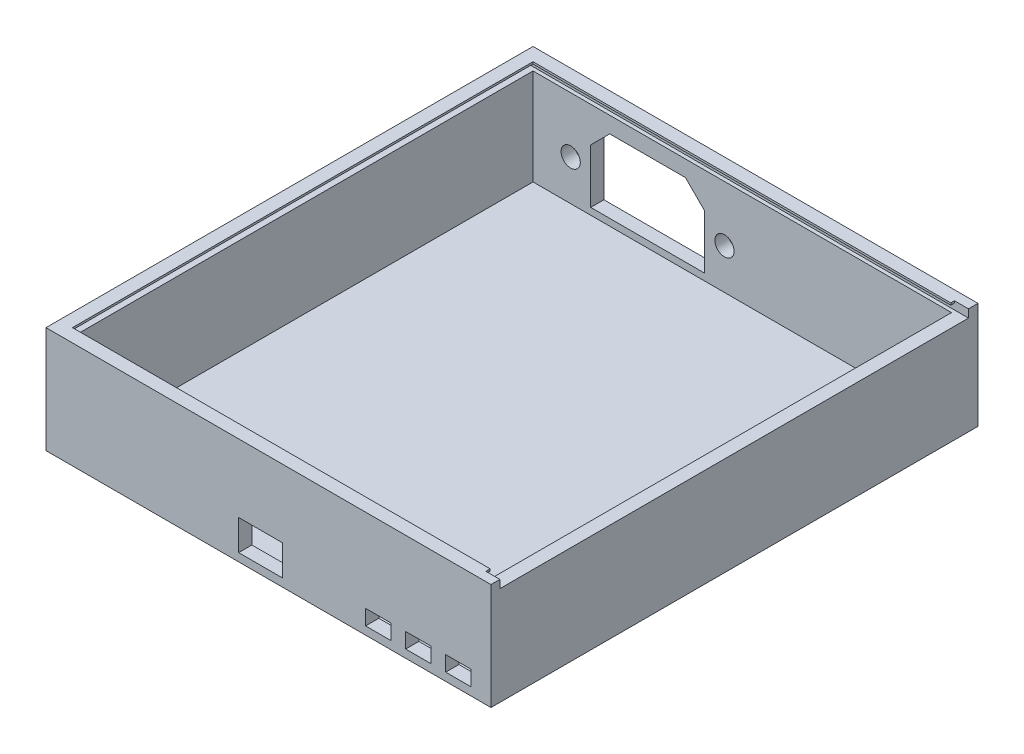
SolidWorks part; units mm, degrees
ref_plane "Front Plane" through (0, 0, 0) normal (0, 0, 1) x (1, 0, 0)
ref_plane "Top Plane" through (0, 0, 0) normal (0, 1, 0) x (1, 0, 0)
ref_plane "Right Plane" through (0, 0, 0) normal (1, 0, 0) x (0, 0, -1)
sketch "Sketch1" plane through (0, 0, 0) normal (0, 1, 0) x (1, 0, 0)
  line L2 (-55.55, -60.8) -> (55.55, -60.8)
  line L3 (-55.55, -60.8) -> (-55.55, 60.8)
  line L4 (-55.55, 60.8) -> (55.55, 60.8)
  line L5 (55.55, -60.8) -> (55.55, 60.8)
  line L6 (-55.55, -60.8) -> (55.55, 60.8) construction
  line L7 (-55.55, 60.8) -> (55.55, -60.8) construction
  point P1 (0, 0)
  dimension "D1" = 111.1
  dimension "D2" = 121.6
extrude "Boss-Extrude1" add sketch "Sketch1" along normal blind 26.6
sketch "Sketch2" plane through (0, 26.6, 0) normal (0, 1, 0) x (1, 0, 0)
  line L1 (-52.25, 57.5) -> (52.25, 57.5)
  line L2 (-52.25, 57.5) -> (-52.25, -57.5)
  line L3 (-52.25, -57.5) -> (52.25, -57.5)
  line L4 (52.25, 57.5) -> (52.25, -57.5)
  line L5 (-52.25, 57.5) -> (52.25, -57.5) construction
  line L6 (-52.25, -57.5) -> (52.25, 57.5) construction
  point P0 (0, 0)
  dimension "D1" = 104.5
  dimension "D2" = 115
extrude "Cut-Extrude1" cut sketch "Sketch2" against normal blind 26
sketch "Sketch5" plane through (0, 0, -60.8) normal (0, 0, -1) x (-1, 0, 0)
  line L5 (13.1156, 19.4826) -> (14.2, 19.4826) construction
  line L6 (9.45, 2.3) -> (37.85, 2.3)
  line L8 (9.45, 2.3) -> (9.45, 15.817)
  line L9 (14.2, 20.567) -> (33.1, 20.567)
  line L10 (37.85, 2.3) -> (37.85, 15.817)
  line L11 (34.1844, 19.4826) -> (33.1, 19.4826) construction
  line L12 (14.2, 20.567) -> (9.45, 15.817)
  line L13 (33.1, 20.567) -> (37.85, 15.817)
  line L14 (55.55, 26.6) -> (55.55, 0) construction
  line L15 (-55.55, 0) -> (55.55, 0) construction
  circle A0 centre (42.85, 10.7) radius 2.4
  circle A1 centre (4.45, 10.7) radius 2.4
  dimension "D1" = 4.8
  dimension "D2" = 4.8
  dimension "D3" = 5
  dimension "D4" = 5
  dimension "D5" = 8.4
  dimension "D6" = 8.4
  dimension "D7" = 12.7
  dimension "D8" = 2.3
extrude "Cut-Extrude3" cut sketch "Sketch5" against normal blind 4
sketch "Sketch7" plane through (0, 0, 60.8) normal (0, 0, 1) x (1, 0, 0)
  line L0 (55.55, 26.6) -> (55.55, 0) construction
  line L1 (44.25, 2) -> (50.55, 2)
  line L2 (44.25, 2) -> (44.25, 5.8)
  line L3 (44.25, 5.8) -> (50.55, 5.8)
  line L4 (50.55, 2) -> (50.55, 5.8)
  line L5 (-55.55, 0) -> (55.55, 0) construction
  line L7 (34.25, 2) -> (40.55, 2)
  line L8 (34.25, 2) -> (34.25, 5.8)
  line L9 (34.25, 5.8) -> (40.55, 5.8)
  line L10 (40.55, 2) -> (40.55, 5.8)
  line L11 (24.25, 2) -> (30.55, 2)
  line L12 (24.25, 2) -> (24.25, 5.8)
  line L13 (24.25, 5.8) -> (30.55, 5.8)
  line L14 (30.55, 2) -> (30.55, 5.8)
  line L15 (-7.45, 9.6) -> (3.55, 9.6)
  line L16 (-7.45, 9.6) -> (-7.45, 2)
  line L17 (-7.45, 2) -> (3.55, 2)
  line L18 (3.55, 9.6) -> (3.55, 2)
  point P12 (37.4, 2)
  dimension "D1" = 5
  dimension "D2" = 6.3
  dimension "D3" = 3.8
  dimension "D4" = 2
  dimension "D5" = 3.8
  dimension "D6" = 6.3
  dimension "D7" = 15
  dimension "D8" = 2
  dimension "D9" = 6.3
  dimension "D10" = 3.8
  dimension "D11" = 25
  dimension "D12" = 2
  dimension "D13" = 11
  dimension "D14" = 7.6
  dimension "D15" = 2
  dimension "D16" = 52
extrude "Cut-Extrude4" cut sketch "Sketch7" against normal blind 4
sketch "Sketch8" plane through (55.55, 0, 0) normal (1, 0, 0) x (0, 0, -1)
  line L0 (-60.8, 26.6) -> (60.8, 26.6) construction
  line L1 (-58.5729, 24.6) -> (58.4271, 24.6)
  line L2 (-58.5729, 24.6) -> (-58.5729, 26.1)
  line L3 (-58.5729, 26.1) -> (58.4271, 26.1)
  line L4 (58.4271, 24.6) -> (58.4271, 26.1)
  dimension "D1" = 117
  dimension "D2" = 1.5
  dimension "D3" = 0.5
extrude "Cut-Extrude5" cut sketch "Sketch8" against normal blind 110
sketch "Sketch9" plane through (55.55, 0, 0) normal (1, 0, 0) x (0, 0, -1)
  line L0 (-60.8, 26.6) -> (60.8, 26.6) construction
  line L1 (-58.5729, 26.1) -> (58.4271, 26.1)
  line L2 (-58.5729, 26.1) -> (-58.5729, 26.6)
  line L3 (-58.5729, 26.6) -> (58.4271, 26.6)
  line L4 (58.4271, 26.1) -> (58.4271, 26.6)
  line L5 (-58.5729, 26.1) -> (-58.5729, 24.6) construction
  dimension "D1" = 117
  dimension "D2" = 0.5
  dimension "D3" = 0
  dimension "0" = 0
extrude "Cut-Extrude6" cut sketch "Sketch9" against normal blind 3.5
